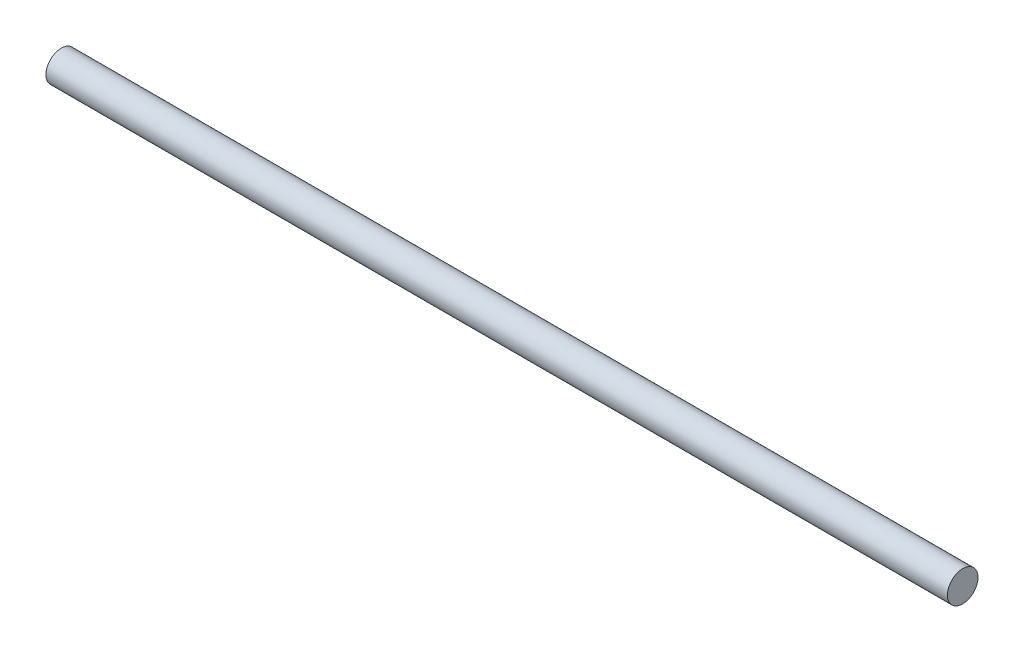
SolidWorks part; units mm, degrees
material "Stainless Steel (ferritic)"
ref_plane "Front Plane" through (0, 0, 0) normal (0, 0, 1) x (1, 0, 0)
ref_plane "Top Plane" through (0, 0, 0) normal (0, 1, 0) x (1, 0, 0)
ref_plane "Right Plane" through (0, 0, 0) normal (1, 0, 0) x (0, 0, -1)
sketch "Sketch1" plane through (0, 0, 0) normal (1, 0, 0) x (0, 0, -1)
  circle A0 centre (0, 0) radius 1.5
  dimension "D1" = 3
extrude "Boss-Extrude1" add sketch "Sketch1" along normal blind 88.49 contours A0
